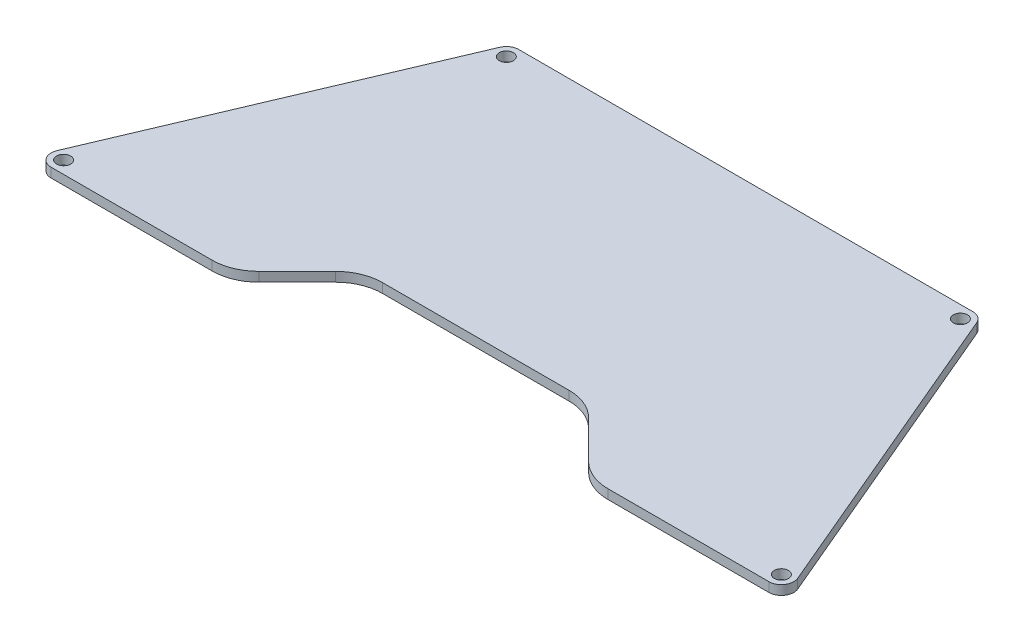
SolidWorks part; units mm, degrees
ref_plane "前视基准面" through (0, 0, 0) normal (0, 0, 1) x (1, 0, 0)
ref_plane "上视基准面" through (0, 0, 0) normal (0, 1, 0) x (1, 0, 0)
ref_plane "右视基准面" through (0, 0, 0) normal (1, 0, 0) x (0, 0, -1)
sketch "草图1" plane through (0, 0, 0) normal (0, 1, 0) x (1, 0, 0)
  line L0 (0, 0) -> (161.0974, 0) construction
  line L1 (28.067, 83.2776) -> (28.067, -24.133) construction
  line L2 (76.3905, -38.2145) -> (76.3905, 78.5009) construction
  line L3 (-2.4396, 1.0348) -> (25.6274, 67.2018)
  line L4 (28.067, 68.817) -> (124.714, 68.817)
  line L5 (127.1536, 67.2018) -> (155.2206, 1.0348)
  line L6 (0, -2.65) -> (38.3905, -2.65)
  line L7 (100.3905, 11.35) -> (52.3905, 11.35)
  line L8 (-4.3863, 11.35) -> (164.1065, 11.35) construction
  line L9 (100.3905, 11.35) -> (114.3905, -2.65)
  line L10 (52.3905, 11.35) -> (38.3905, -2.65)
  line L11 (114.3905, -2.65) -> (152.781, -2.65)
  circle A0 centre (0, 0) radius 1.5
  circle A1 centre (152.781, 0) radius 1.5
  circle A2 centre (28.067, 66.167) radius 1.5
  circle A4 centre (124.714, 66.167) radius 1.5
  arc A5 (-2.4396, 1.0348) -> (0, -2.65) centre (0, 0) ccw
  arc A6 (152.781, -2.65) -> (155.2206, 1.0348) centre (152.781, 0) ccw
  arc A7 (28.067, 68.817) -> (25.6274, 67.2018) centre (28.067, 66.167) ccw
  arc A8 (124.714, 68.817) -> (127.1536, 67.2018) centre (124.714, 66.167) cw
  point P27 (76.3905, 11.35)
  dimension "D1" = 3
  dimension "D5" = 3
  dimension "D6" = 5.3
  dimension "D7" = 5.3
  dimension "D8" = 5.3
  dimension "D9" = 14
  dimension "D2" = 152.781
  dimension "D3" = 66.167
  dimension "D4" = 28.067
  dimension "D10" = 24
  dimension "D11" = 45
extrude "凸台-拉伸1" add sketch "草图1" along normal blind 2
fillet "圆角1" radius 10 1 edges at (38.3905, 1, 2.65)
fillet "圆角2" radius 10 1 edges at (52.3905, 1, -11.35)
fillet "圆角3" radius 10 1 edges at (100.3905, 1, -11.35)
fillet "圆角4" radius 10 1 edges at (114.3905, 1, 2.65)
